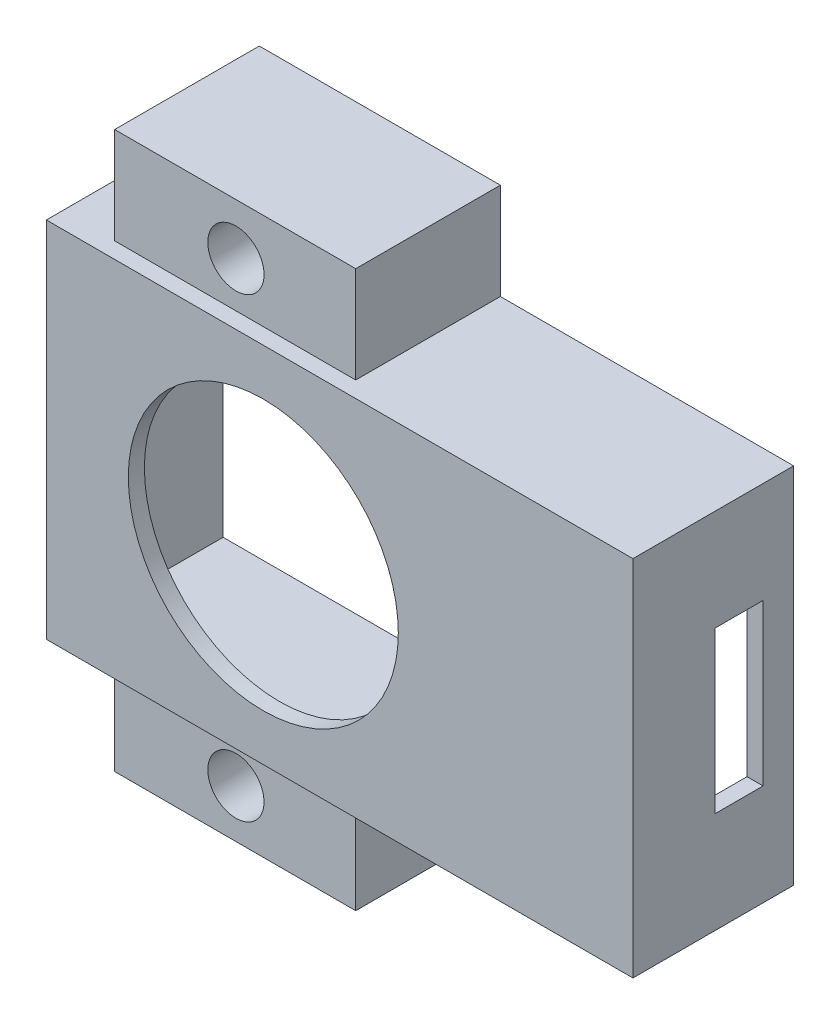
SolidWorks part; units mm, degrees
ref_plane "Front Plane" through (0, 0, 0) normal (0, 0, 1) x (1, 0, 0)
ref_plane "Top Plane" through (0, 0, 0) normal (0, 1, 0) x (1, 0, 0)
ref_plane "Right Plane" through (0, 0, 0) normal (1, 0, 0) x (0, 0, -1)
sketch "Sketch1" plane through (0, 0, 0) normal (0, 0, 1) x (1, 0, 0)
  line L1 (-18.25, -11.3) -> (18.25, -11.3)
  line L2 (-18.25, -11.3) -> (-18.25, 11.3)
  line L3 (-18.25, 11.3) -> (18.25, 11.3)
  line L4 (18.25, -11.3) -> (18.25, 11.3)
  line L5 (-18.25, -11.3) -> (18.25, 11.3) construction
  line L6 (-18.25, 11.3) -> (18.25, -11.3) construction
  point P0 (0, 0)
  dimension "D1" = 36.5
  dimension "D2" = 22.6
extrude "Boss-Extrude2" add sketch "Sketch1" along normal blind 10
shell "Shell2" thickness 1
sketch "Sketch2" plane through (0, 0, 9) normal (0, 0, -1) x (-1, 0, 0)
  line L0 (17.25, 10.3) -> (17.25, -10.3) construction
  circle A0 centre (4.75, 0) radius 8.4
  dimension "D1" = 16.8
  dimension "D2" = 12.5
extrude "Cut-Extrude1" cut sketch "Sketch2" against normal blind 10
sketch "Sketch3" plane through (18.25, 0, 0) normal (1, 0, 0) x (0, 0, -1)
  line L0 (0, -11.3) -> (0, 11.3) construction
  line L1 (-1.9, -5) -> (-4.9, -5)
  line L2 (-1.9, -5) -> (-1.9, 5)
  line L3 (-1.9, 5) -> (-4.9, 5)
  line L4 (-4.9, -5) -> (-4.9, 5)
  line L5 (-1.9, -5) -> (-4.9, 5) construction
  line L6 (-1.9, 5) -> (-4.9, -5) construction
  point P0 (-3.4, 0)
  dimension "D1" = 10
  dimension "D2" = 3
  dimension "D3" = 1.9
extrude "Cut-Extrude3" cut sketch "Sketch3" against normal blind 10
sketch "Sketch4" plane through (0, 0, 9) normal (0, 0, -1) x (-1, 0, 0)
  line L0 (-18.25, 11.3) -> (18.25, 11.3) construction
  line L1 (0, 11.3) -> (15, 11.3)
  line L2 (0, 11.3) -> (0, 17.3)
  line L3 (0, 17.3) -> (15, 17.3)
  line L4 (15, 11.3) -> (15, 17.3)
  line L5 (18.25, -11.3) -> (-18.25, -11.3) construction
  line L6 (0, -11.3) -> (15, -11.3)
  line L7 (0, -11.3) -> (0, -17.3)
  line L8 (0, -17.3) -> (15, -17.3)
  line L9 (15, -11.3) -> (15, -17.3)
  dimension "D1" = 15
  dimension "D2" = 6
  dimension "D3" = 6
extrude "Boss-Extrude3" add sketch "Sketch4" along normal up to surface (9 mm away) up to face at (0, 0, 0)
sketch "Sketch5" plane through (0, 0, 0) normal (0, 0, -1) x (-1, 0, 0)
  circle A0 centre (7.4553, 14.124) radius 1.75
  circle A1 centre (7.4553, -14.2962) radius 1.75
  point P2 (7.4553, -14.2962)
  dimension "D1" = 3.5
  dimension "D2" = 3.5
extrude "Cut-Extrude4" cut sketch "Sketch5" against normal blind 18
